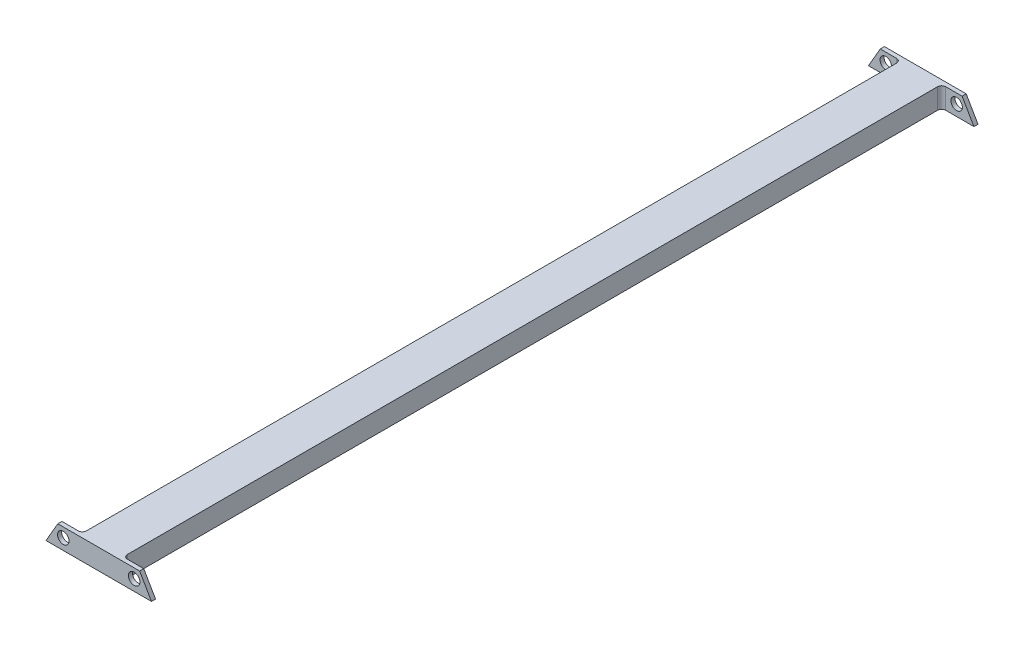
SolidWorks part; units mm, degrees
ref_plane "Płaszczyzna przednia" through (0, 0, 0) normal (0, 0, 1) x (1, 0, 0)
ref_plane "Płaszczyzna górna" through (0, 0, 0) normal (0, 1, 0) x (1, 0, 0)
ref_plane "Płaszczyzna prawa" through (0, 0, 0) normal (1, 0, 0) x (0, 0, -1)
sketch "Szkic1" plane through (0, 0, 0) normal (0, 0, 1) x (1, 0, 0)
  line L0 (0, 0) -> (100, 0)
  line L1 (100, 0) -> (114.4338, -25)
  line L2 (114.4338, -25) -> (-14.4338, -25)
  line L3 (-14.4338, -25) -> (0, 0)
  line L4 (-14.4338, -25) -> (-54.0882, -93.6835) construction
  line L5 (100, 0) -> (144.1247, -76.4263) construction
  circle A0 centre (50, -86.6025) radius 86.6025 construction
  circle A1 centre (93.3013, -11.6025) radius 7
  circle A2 centre (6.6987, -11.6025) radius 7
  point P18 (50, -86.6025)
  dimension "D4" = 14
  dimension "D1" = 100
  dimension "D2" = 60
  dimension "D3" = 25
  dimension "D6" = 60
  dimension "D5" = 2
extrude "Dodanie-wyciągnięcie1" add sketch "Szkic1" along normal blind 5
ref_plane "Płaszczyzna1" through (0, 0, 5) normal (0, 0, 1) x (1, 0, 0)
sketch "Szkic2" plane through (0, 0, 5) normal (0, 0, 1) x (1, 0, 0)
  line L0 (100, 0) -> (0, 0) construction
  line L1 (25, -25) -> (75, -25)
  line L2 (25, -25) -> (25, 0)
  line L3 (25, 0) -> (75, 0)
  line L4 (75, -25) -> (75, 0)
  line L5 (25, -25) -> (75, 0) construction
  line L6 (25, 0) -> (75, -25) construction
  line L7 (-14.4338, -25) -> (114.4338, -25) construction
  point P0 (50, -12.5)
  dimension "D1" = 50
  dimension "D2" = 50
extrude "Dodanie-wyciągnięcie2" add sketch "Szkic2" along normal blind 1000
ref_plane "Płaszczyzna2" through (0, 0, 1005) normal (0, 0, 1) x (1, 0, 0)
sketch "Szkic3" plane through (0, 0, 1005) normal (0, 0, 1) x (1, 0, 0)
  line L0 (-14.4338, -25) -> (25, -25) construction
  line L1 (25, -25) -> (75, -25) construction
  line L2 (75, -25) -> (114.4338, -25) construction
  line L3 (25, 0) -> (75, 0) construction
  line L4 (114.4338, -25) -> (100, 0) construction
  line L5 (100, 0) -> (75, 0) construction
  line L6 (25, 0) -> (0, 0) construction
  line L7 (0, 0) -> (-14.4338, -25) construction
  line L8 (-14.4338, -25) -> (25, -25)
  line L9 (25, -25) -> (75, -25)
  line L10 (75, -25) -> (114.4338, -25)
  line L11 (25, 0) -> (75, 0)
  line L12 (114.4338, -25) -> (100, 0)
  line L13 (100, 0) -> (75, 0)
  line L14 (25, 0) -> (0, 0)
  line L15 (0, 0) -> (-14.4338, -25)
  circle A0 centre (93.3013, -11.6025) radius 7 construction
  circle A1 centre (6.6987, -11.6025) radius 7 construction
  circle A2 centre (93.3013, -11.6025) radius 7
  circle A3 centre (6.6987, -11.6025) radius 7
extrude "Dodanie-wyciągnięcie3" add sketch "Szkic3" along normal blind 5
fillet "Zaokrąglenie1" radius 5 1 edges at (25, -12.5, 5)
fillet "Zaokrąglenie2" radius 5 1 edges at (75, -12.5, 5)
fillet "Zaokrąglenie3" radius 5 1 edges at (75, -12.5, 1005)
fillet "Zaokrąglenie4" radius 5 1 edges at (25, -12.5, 1005)
